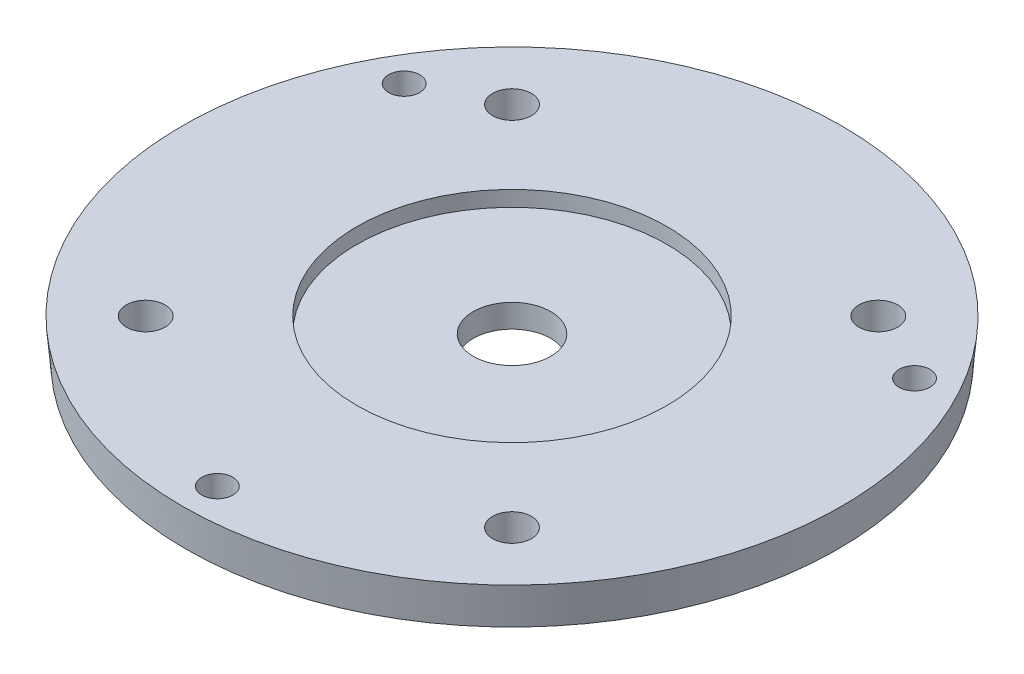
SolidWorks part; units mm, degrees
ref_plane "Front Plane" through (0, 0, 0) normal (0, 0, 1) x (1, 0, 0)
ref_plane "Top Plane" through (0, 0, 0) normal (0, 1, 0) x (1, 0, 0)
ref_plane "Right Plane" through (0, 0, 0) normal (1, 0, 0) x (0, 0, -1)
sketch "Sketch1" plane through (0, 0, 0) normal (0, 1, 0) x (1, 0, 0)
  circle A0 centre (0, 0) radius 42.5
  dimension "D1" = 85
extrude "Boss-Extrude1" add sketch "Sketch1" against normal blind 5 draft 5
sketch "Sketch2" plane through (0, 0, 0) normal (0, 1, 0) x (1, 0, 0)
  circle A0 centre (23.62, 23.62) radius 2.5
  circle A1 centre (23.62, -23.62) radius 2.5
  circle A2 centre (-23.62, -23.62) radius 2.5
  circle A3 centre (-23.62, 23.62) radius 2.5
  circle A4 centre (0, 0) radius 5
  point P0 (0, 0)
extrude "Cut-Extrude2" cut sketch "Sketch2" against normal through all
sketch "Sketch3" plane through (0, 0, 0) normal (0, 1, 0) x (1, 0, 0)
  circle A1 centre (0, 0) radius 20
  dimension "D1" = 40
extrude "Cut-Extrude3" cut sketch "Sketch3" against normal blind 2
sketch "Sketch5" plane through (0, 0, 0) normal (0, 1, 0) x (1, 0, 0)
  line L0 (0, 0) -> (0, -38) construction
  circle A0 centre (0, -38) radius 2
  circle A1 centre (-32.909, 19) radius 2
  circle A2 centre (32.909, 19) radius 2
  point P11 (0, 0)
  dimension "D2" = 4
  dimension "D1" = 38
  dimension "D3" = 3
extrude "Cut-Extrude4" cut sketch "Sketch5" against normal up to surface (5 mm away) up to face at (0, -5, 5)
